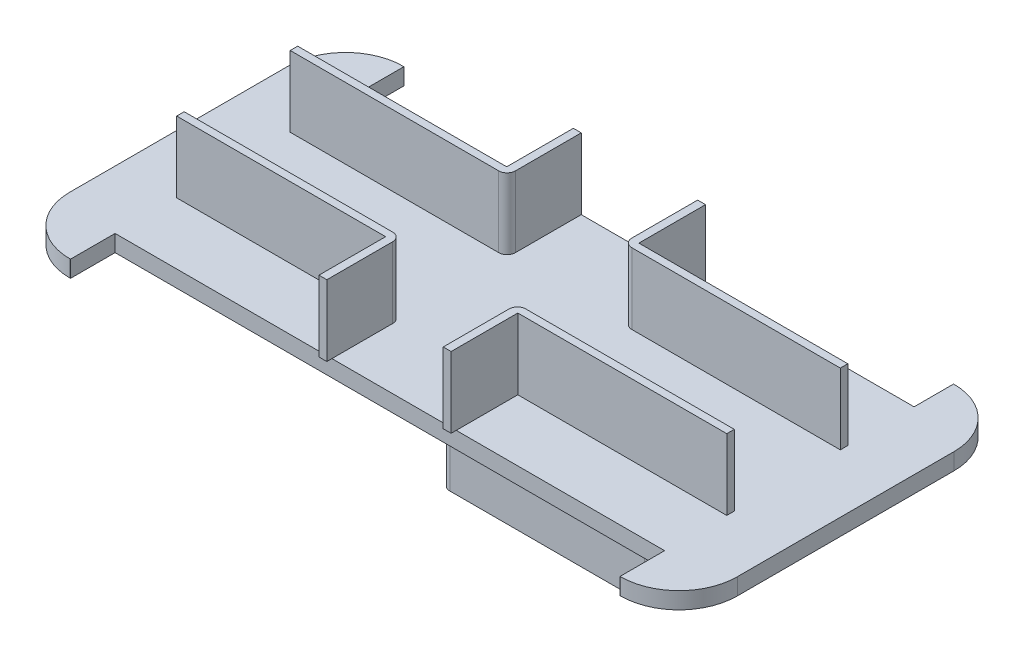
SolidWorks part; units mm, degrees
material "PVC Rigid"
ref_plane "Front Plane" through (0, 0, 0) normal (0, 0, 1) x (1, 0, 0)
ref_plane "Top Plane" through (0, 0, 0) normal (0, 1, 0) x (1, 0, 0)
ref_plane "Right Plane" through (0, 0, 0) normal (1, 0, 0) x (0, 0, -1)
sketch "Sketch1" plane through (0, 0, 0) normal (0, 1, 0) x (1, 0, 0)
  line L1 (101.6, 50.8) -> (-101.6, 50.8)
  line L2 (101.6, 50.8) -> (101.6, -50.8)
  line L3 (101.6, -50.8) -> (-101.6, -50.8)
  line L4 (-101.6, 50.8) -> (-101.6, -50.8)
  line L5 (101.6, 50.8) -> (-101.6, -50.8) construction
  line L6 (101.6, -50.8) -> (-101.6, 50.8) construction
  point P0 (0, 0)
  dimension "D1" = 203.2
  dimension "D2" = 101.6
extrude "Boss-Extrude1" add sketch "Sketch1" along normal blind 5.08
sketch "Sketch2" plane through (0, 5.08, 0) normal (0, 1, 0) x (1, 0, 0)
  line L0 (-84.074, 50.8) -> (-83.82, 50.8)
  line L1 (101.6, 50.8) -> (-101.6, 50.8) construction
  line L2 (-83.82, 50.8) -> (-83.82, 38.7677)
  line L3 (-83.82, 38.7677) -> (83.6938, 38.7677)
  line L4 (83.6938, 38.7677) -> (83.6938, 50.8)
  line L5 (83.6938, 50.8) -> (83.82, 50.8)
  line L6 (101.6, 33.02) -> (101.6, -33.02)
  line L7 (83.82, -50.8) -> (83.6473, -50.8)
  line L8 (-101.6, -50.8) -> (101.6, -50.8) construction
  line L9 (83.6473, -50.8) -> (83.6473, -37.2158)
  line L10 (83.6473, -37.2158) -> (-83.82, -37.2158)
  line L11 (-83.82, -37.2158) -> (-83.82, -50.8)
  line L12 (-83.82, -50.8) -> (-84.074, -50.8)
  line L13 (-101.6, 50.8) -> (-101.6, -50.8) construction
  line L14 (-101.6, -33.274) -> (-101.6, 33.274)
  line L15 (-83.82, 50.8) -> (-83.82, 50.4434)
  line L17 (83.6938, 50.4434) -> (83.6938, 38.7677)
  arc A0 (101.6, 33.02) -> (83.82, 50.8) centre (83.82, 33.02) ccw
  arc A1 (83.82, -50.8) -> (101.6, -33.02) centre (83.82, -33.02) ccw
  arc A2 (-101.6, 33.274) -> (-84.074, 50.8) centre (-84.074, 33.274) cw
  arc A3 (-101.6, -33.274) -> (-84.074, -50.8) centre (-84.074, -33.274) ccw
  point P23 (101.6, 50.8)
  point P26 (101.6, -50.8)
  point P29 (-101.6, 50.8)
  point P32 (-101.6, -50.8)
  line M17 (-101.6, 50.8) -> (-101.6, -50.8)
  line M18 (-101.6, -50.8) -> (101.6, -50.8)
  line M19 (101.6, -50.8) -> (101.6, 50.8)
  line M20 (101.6, 50.8) -> (-101.6, 50.8)
  dimension "D1" = 17.78
  dimension "D2" = 17.78
  dimension "D5" = 17.526
  dimension "D6" = 17.526
  dimension "D3" = 17.78
  dimension "D4" = 17.78
extrude "Cut-Extrude4" cut sketch "Sketch2" against normal through all contours L3 L4 L2 M20 | A0 M19 M20 | A1 M18 M19 | A3 M17 M18 | A2 M17 M20 | L10 L11 L9 M18
sketch "Sketch4" plane through (0, 5.08, 0) normal (0, 1, 0) x (1, 0, 0)
  line L0 (-83.82, 16.1617) -> (-17.7368, 16.1617)
  line L1 (-83.82, 38.7677) -> (83.6938, 38.7677) construction
  line L2 (-20.1455, 38.7677) -> (-20.1455, 18.4477)
  line L3 (-20.1455, 18.4477) -> (-83.82, 18.4477)
  line L4 (-17.7368, 16.1617) -> (-17.7368, 38.7677)
  line L5 (-83.82, 16.1617) -> (-83.82, 18.4477)
  line L6 (-20.1455, 38.7677) -> (-17.7368, 38.7677)
  dimension "D1" = 2.4087
  dimension "D2" = 2.286
  dimension "D3" = 63.6745
extrude "Boss-Extrude2" add sketch "Sketch4" along normal blind 21.59
fillet "Fillet1" radius 2.54 1 edges at (-17.7368, 15.875, -16.1617)
mirror "Mirror1" about plane through (0, 0, 0) normal (1, 0, 0) of "Boss-Extrude2"
fillet "Fillet2" radius 2.54 1 edges at (17.7368, 15.875, -16.1617)
mirror "Mirror3" about plane through (0, 0, 0) normal (0, 0, 1) of "Mirror1", "Boss-Extrude2"
fillet "Fillet3" radius 2.54 2 edges at (17.7368, 15.875, 16.1617) (-17.7368, 15.875, 16.1617)
sketch "Sketch5" plane through (0, 0, 0) normal (0, -1, 0) x (1, 0, 0)
  line L1 (71.604, -28.7949) -> (7.2261, -28.7949)
  line L2 (71.604, -28.7949) -> (71.604, 28.7949)
  line L3 (71.604, 28.7949) -> (7.2261, 28.7949)
  line L4 (7.2261, -28.7949) -> (7.2261, 28.7949)
  line L5 (71.604, -28.7949) -> (7.2261, 28.7949) construction
  line L6 (71.604, 28.7949) -> (7.2261, -28.7949) construction
  point P0 (39.4151, 0)
extrude "Boss-Extrude4" add sketch "Sketch5" along normal blind 20.32
sketch "Sketch6" plane through (0, -20.32, 0) normal (0, -1, 0) x (1, 0, 0)
  line L1 (9.6348, -26.1672) -> (69.6333, -26.1672)
  line L2 (9.6348, -26.1672) -> (9.6348, 26.1672)
  line L3 (9.6348, 26.1672) -> (69.6333, 26.1672)
  line L4 (69.6333, -26.1672) -> (69.6333, 26.1672)
extrude "Cut-Extrude5" cut sketch "Sketch6" against normal blind 20.32
sketch "Sketch7" plane through (7.2261, 0, 0) normal (-1, 0, 0) x (0, 0, 1)
  line L0 (28.7949, 0) -> (-28.7949, 0) construction
  line L1 (-18.0652, 0) -> (19.2696, 0)
  line L2 (-18.0652, 0) -> (-18.0652, -5.2007)
  line L3 (-18.0652, -5.2007) -> (19.2696, -5.2007)
  line L4 (19.2696, 0) -> (19.2696, -5.2007)
extrude "Cut-Extrude6" cut sketch "Sketch7" against normal through all
sketch "Sketch8" plane through (0, 0, -28.7949) normal (0, 0, -1) x (-1, 0, 0)
  line L0 (-7.2261, 0) -> (-71.604, 0) construction
  line L1 (-62.4072, 0) -> (-16.6419, 0)
  line L2 (-62.4072, 0) -> (-62.4072, -5.9124)
  line L3 (-62.4072, -5.9124) -> (-16.6419, -5.9124)
  line L4 (-16.6419, 0) -> (-16.6419, -5.9124)
extrude "Cut-Extrude7" cut sketch "Sketch8" against normal through all
fillet "Fillet4" radius 2.54 4 edges at (71.604, -10.16, 28.7949) (7.2261, -10.16, 28.7949) (71.604, -10.16, -28.7949) (7.2261, -10.16, -28.7949)
